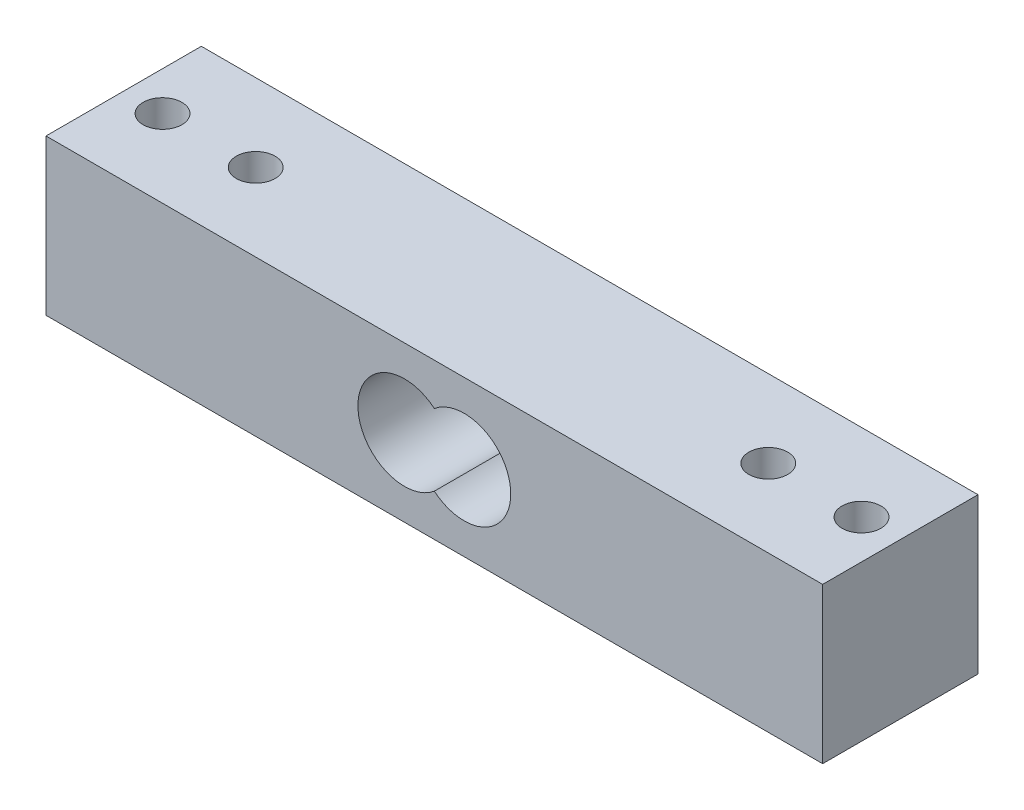
SolidWorks part; units mm, degrees
material "Aleación 1060"
ref_plane "Front" through (0, 0, 0) normal (0, 0, 1) x (1, 0, 0)
ref_plane "Top" through (0, 0, 0) normal (0, 1, 0) x (1, 0, 0)
ref_plane "Right" through (0, 0, 0) normal (1, 0, 0) x (0, 0, -1)
sketch "Croquis1" plane through (0, 0, 0) normal (0, 0, 1) x (1, 0, 0)
  line L0 (0, 0) -> (-1.9205, 0) construction
  line L1 (25, 5) -> (-25, 5)
  line L2 (25, 5) -> (25, -5)
  line L3 (25, -5) -> (-25, -5)
  line L4 (-25, 5) -> (-25, -5)
  line L5 (25, 5) -> (-25, -5) construction
  line L6 (25, -5) -> (-25, 5) construction
  line L7 (0, 0) -> (0, 2.3047) construction
  arc A0 (0, 2.3047) -> (0, -2.3047) centre (-1.9205, 0) ccw
  arc A1 (0, 2.3047) -> (0, -2.3047) centre (1.9205, 0) cw
  point P0 (0, 0)
  dimension "D1" = 50
  dimension "D4" = 3
  dimension "D2" = 10
extrude "Saliente-Extruir1" add sketch "Croquis1" along normal blind 10
hole_wizard "Perforador para roscar para macho de roscar para M32" positions "Croquis2" profile "Croquis3" hole size "M3" standard "ISO" end condition through all
sketch "Croquis2" plane through (0, 5, 0) normal (0, 1, 0) x (1, 0, 0)
  line L0 (-25, -10) -> (-25, 0) construction
  point P0 (-22.5, -5)
  point P2 (-16.5, -5)
  point P9 (-25, -5)
  dimension "D1" = 2.5
  dimension "D2" = 6
sketch "Croquis3" plane through (-22.5, 5, 5) normal (1, 0, 0) x (0, 0, 1)
  line L0 (0, 0) -> (0, 10)
  line L1 (0, 10) -> (1.25, 10)
  line L2 (1.25, 10) -> (1.25, 0)
  line L5 (1.25, 0) -> (0, 0)
  line L11 (0, -6.35) -> (0, 107.95) construction
  dimension "Diámetro de taladro hasta el siguiente" = 2.5
  dimension "Profundidad de taladro hasta el siguiente" = 10
hole_wizard "Perforador para roscar para macho de roscar para M33" positions "Croquis4" profile "Croquis5" size "M3" standard "ISO" slot yes end condition through all
sketch "Croquis4" plane through (0, 5, 0) normal (0, 1, 0) x (1, 0, 0)
  line L0 (25, -10) -> (25, 0) construction
  point P0 (22.5, -5)
  point P2 (16.5, -5)
  point P7 (25, -5)
  dimension "D1" = 6
  dimension "D2" = 2.5
sketch "Croquis5" plane through (22.5, 5, 5) normal (1, 0, 0) x (0, 0, 1)
  line L0 (0, 0) -> (0, 10)
  line L1 (0, 10) -> (1.25, 10)
  line L2 (1.25, 10) -> (1.25, 0)
  line L5 (1.25, 0) -> (0, 0)
  line L11 (0, -6.35) -> (0, 107.95) construction
  dimension "Diámetro de taladro hasta el siguiente" = 2.5
  dimension "Profundidad de taladro hasta el siguiente" = 10
sketch "Croquis6" plane through (0, 5, 0) normal (0, 1, 0) x (1, 0, 0)
  line L0 (25, -10) -> (-25, -10) construction
  line L1 (25, 0) -> (15, 0)
  line L2 (25, 0) -> (25, -10)
  line L3 (25, -10) -> (15, -10)
  line L4 (15, 0) -> (15, -10)
  dimension "D1" = 10
extrude "Saliente-Extruir2" [suppressed] add sketch "Croquis6" along normal blind 2
sketch "Croquis7" plane through (0, -5, 0) normal (0, -1, 0) x (1, 0, 0)
  line L1 (-40, -1.5) -> (-30, -1.5)
  line L2 (-40, -1.5) -> (-40, 11.5)
  line L3 (-40, 11.5) -> (-30, 11.5)
  line L4 (-30, -1.5) -> (-30, 11.5)
  line L5 (-22.5, 5) -> (-30, 5) construction
  point P7 (-30, 5)
  dimension "D1" = 10
  dimension "D2" = 13
extrude "Saliente-Extruir3" [suppressed] add sketch "Croquis7" along normal blind 2
